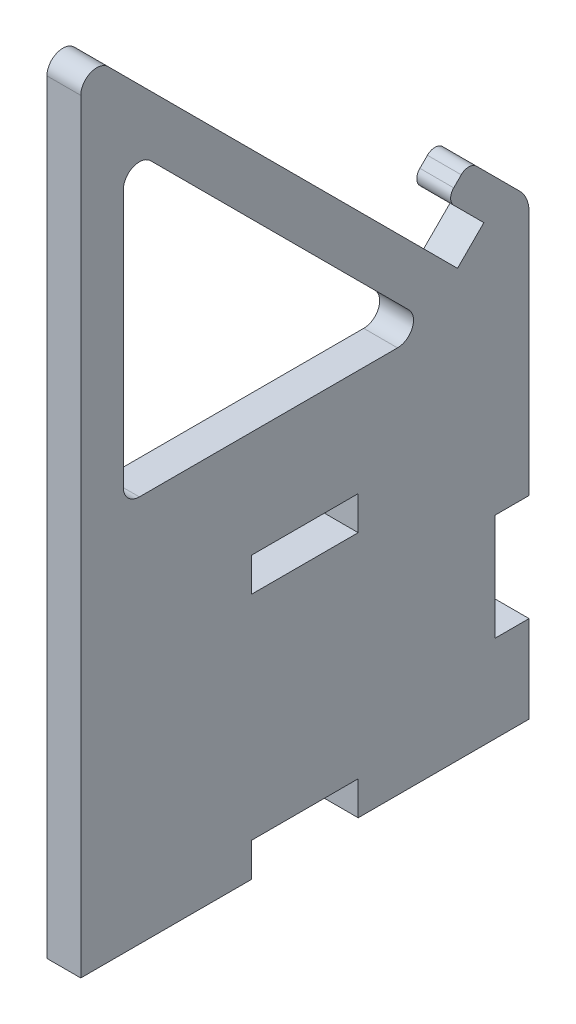
SolidWorks part; units mm, degrees
ref_plane "Plan de face" through (0, 0, 0) normal (0, 0, 1) x (1, 0, 0)
ref_plane "Plan de dessus" through (0, 0, 0) normal (0, 1, 0) x (1, 0, 0)
ref_plane "Plan de droite" through (0, 0, 0) normal (1, 0, 0) x (0, 0, -1)
sketch "Esquisse1" plane through (0, 0, 0) normal (1, 0, 0) x (0, 0, -1)
  line L0 (-42.0729, 0) -> (42.0729, 0)
  line L1 (42.0729, 0) -> (42.0729, 84.9497)
  line L2 (42.0729, 84.9497) -> (30.7591, 96.2635)
  line L3 (30.7591, 96.2635) -> (26.5165, 92.0208)
  line L4 (26.5165, 92.0208) -> (33.5876, 84.9497)
  line L5 (33.5876, 84.9497) -> (28.6378, 80)
  line L6 (28.6378, 80) -> (-42.0729, 150.7107)
  line L7 (-42.0729, 150.7107) -> (-42.0729, 0)
  point P2 (-17.9998, 6.3661)
  point P9 (30.052, 88.4853)
  point P10 (0, 0)
  point P11 (0, 0)
  point P12 (0, 0)
  dimension "D1" = 45
  dimension "D2" = 7
  dimension "D3" = 6
  dimension "D4" = 80
  dimension "D5" = 100
  dimension "D6" = 10
extrude "Boss.-Extru.1" add sketch "Esquisse1" along normal blind 6.35
sketch "Esquisse2" plane through (6.35, 0, 0) normal (1, 0, 0) x (0, 0, -1)
  line L0 (-42.0729, 0) -> (42.0729, 0) construction
  line L1 (-10, 0) -> (10, 0)
  line L2 (-10, 0) -> (-10, 6.35)
  line L3 (-10, 6.35) -> (10, 6.35)
  line L4 (10, 0) -> (10, 6.35)
  line L15 (-10, 52.7) -> (10, 52.7)
  line L16 (-10, 52.7) -> (-10, 46.35)
  line L17 (-10, 46.35) -> (10, 46.35)
  line L18 (10, 52.7) -> (10, 46.35)
  line L19 (42.0729, 0) -> (42.0729, 84.9497) construction
  line L29 (42.0729, 36.35) -> (35.7229, 36.35)
  line L30 (42.0729, 36.35) -> (42.0729, 16.35)
  line L31 (42.0729, 16.35) -> (35.7229, 16.35)
  line L32 (35.7229, 36.35) -> (35.7229, 16.35)
  point P6 (0, 0)
  point P7 (27.6491, 16.35)
  point P22 (35.7229, 26.35)
  dimension "D1" = 20
  dimension "D3" = 6.35
  dimension "D5" = 40
  dimension "D6" = 26.35
extrude "Enlèv. mat.-Extru.1" cut sketch "Esquisse2" against normal through all
fillet "Congé1" radius 6 1 edges at (3.175, 84.9497, -42.0729)
fillet "Congé2" radius 2 2 edges at (3.175, 92.0208, -26.5165) (3.175, 96.2635, -30.7591)
sketch "Esquisse4" plane through (6.35, 0, 0) normal (1, 0, 0) x (0, 0, -1)
  line L0 (24.6241, 72.7) -> (-34.0729, 72.7)
  line L1 (-34.0729, 72.7) -> (-34.0729, 131.397)
  line L2 (-34.0729, 131.397) -> (24.6241, 72.7)
  line L3 (28.6378, 80) -> (-42.0729, 150.7107) construction
  line L4 (-42.0729, 150.7107) -> (-42.0729, 0) construction
  line L5 (10, 52.7) -> (-10, 52.7) construction
  dimension "D1" = 8
  dimension "D2" = 8
  dimension "D3" = 20
extrude "Enlèv. mat.-Extru.2" cut sketch "Esquisse4" against normal through all
fillet "Congé4" radius 3 4 edges at (3.175, 72.7, -24.6241) (3.175, 72.7, 34.0729) (3.175, 131.397, 34.0729) (3.175, 150.7107, 42.0729)
